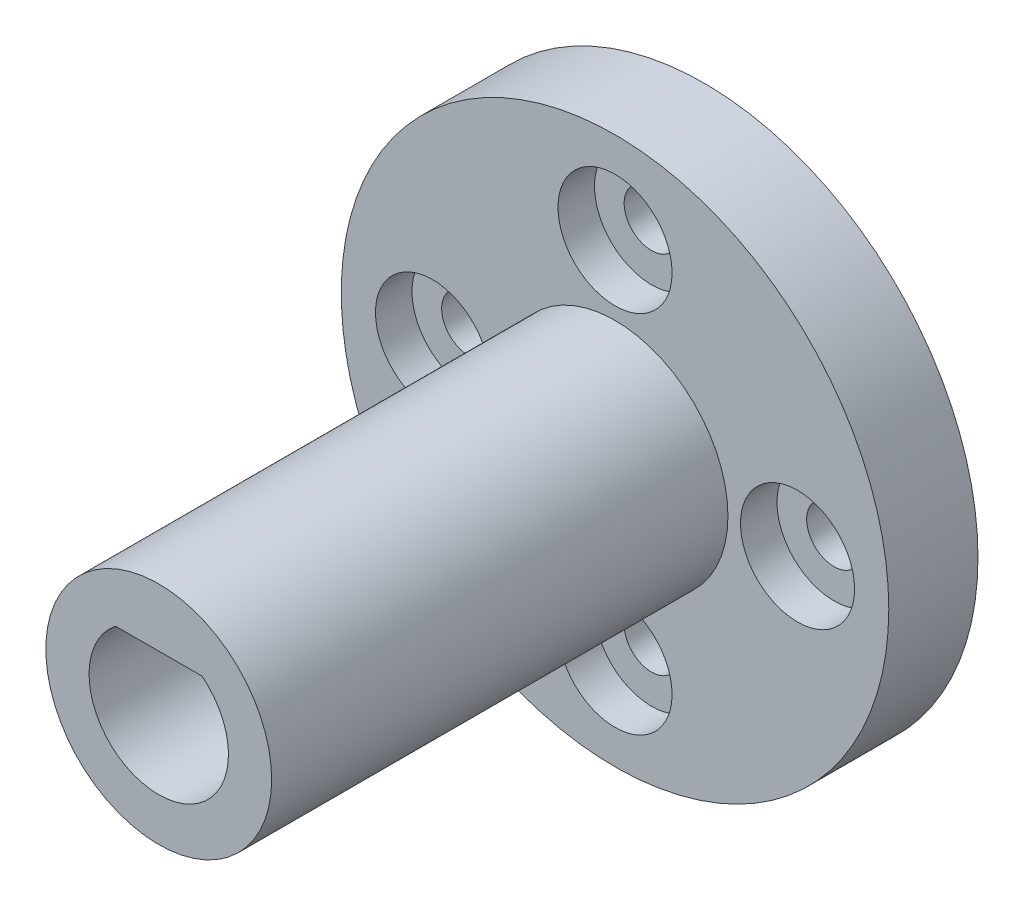
SolidWorks part; units mm, degrees
ref_plane "Plan de face" through (0, 0, 0) normal (0, 0, 1) x (1, 0, 0)
ref_plane "Plan de dessus" through (0, 0, 0) normal (0, 1, 0) x (1, 0, 0)
ref_plane "Plan de droite" through (0, 0, 0) normal (1, 0, 0) x (0, 0, -1)
sketch "Esquisse1" plane through (0, 0, 0) normal (0, 0, 1) x (1, 0, 0)
  circle A0 centre (0, 0) radius 12
  dimension "D1" = 24
extrude "Boss.-Extru.1" add sketch "Esquisse1" along normal blind 3.91
sketch "Esquisse6" plane through (0, 0, 0) normal (0, 0, -1) x (-1, 0, 0)
  circle A0 centre (0, 0) radius 4
  dimension "D1" = 8
extrude "Enlèv. mat.-Extru.2" cut sketch "Esquisse6" against normal blind 1.91
sketch "Esquisse7" plane through (0, 0, 3.91) normal (0, 0, 1) x (1, 0, 0)
  line L0 (1.8966, 2.395) -> (-1.8966, 2.395)
  line L1 (-5.4714, -3.055) -> (6.192, -3.055) construction
  arc A0 (-1.8966, 2.395) -> (1.8966, 2.395) centre (0, 0) ccw
  circle A1 centre (0, 0) radius 4.95
  dimension "D1" = 6.11
  dimension "D3" = 9.9
  dimension "D2" = 5.45
extrude "Boss.-Extru.2" add sketch "Esquisse7" along normal blind 20 contours A1 L1 A0 L0 | L1 A1
hole_wizard "Chambrage pour vis à tête ronde bombée M21" positions "Esquisse10" profile "Esquisse11" counterbore size "M2" standard "Ansi Metric" end condition through all
sketch "Esquisse10" plane through (0, 0, 3.91) normal (0, 0, 1) x (1, 0, 0)
  point P0 (0, 8)
  dimension "D1" = 8
sketch "Esquisse11" plane through (0, 8, 3.91) normal (1, 0, 0) x (0, -1, 0)
  line L0 (0, 0) -> (0, 3.91)
  line L1 (0, 3.91) -> (1.2, 3.91)
  line L3 (1.2, 3.91) -> (1.2, 1.6)
  line L4 (1.2, 1.6) -> (2.5, 1.6)
  line L5 (2.5, 1.6) -> (2.5, 0)
  line L7 (2.5, 0) -> (0, 0)
  line L11 (0, -6.35) -> (0, 107.95) construction
  dimension "Diamètre du perçage jusqu'au prochain" = 2.4
  dimension "Profondeur du perçage jusqu'au prochain" = 3.91
  dimension "Diamètre du chambrage" = 5
  dimension "Profondeur du chambrage" = 1.6
pattern_circular "Répétition circulaire2" count 4 every 90 about axis through (0, 0, 0) along (0, 0, 1) of "Chambrage pour vis à tête ronde bombée M21"
